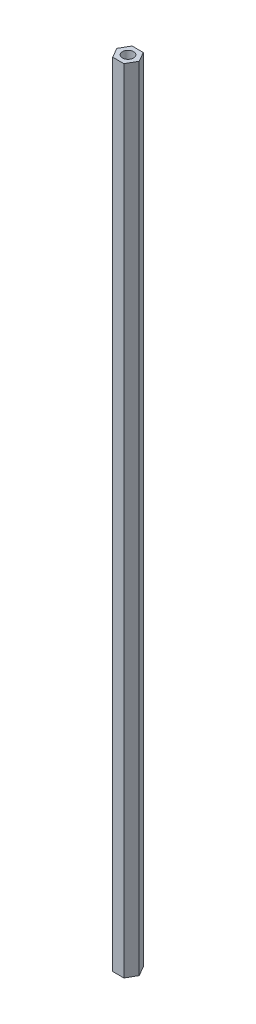
SolidWorks part; units mm, degrees
ref_plane "Front Plane" through (0, 0, 0) normal (0, 0, 1) x (1, 0, 0)
ref_plane "Top Plane" through (0, 0, 0) normal (0, 1, 0) x (1, 0, 0)
ref_plane "Right Plane" through (0, 0, 0) normal (1, 0, 0) x (0, 0, -1)
sketch "Sketch1" plane through (0, 0, 0) normal (0, 1, 0) x (1, 0, 0)
  line L1 (2.0207, 3.5) -> (-2.0207, 3.5)
  line L2 (-2.0207, 3.5) -> (-4.0415, 0)
  line L3 (-4.0415, 0) -> (-2.0207, -3.5)
  line L4 (-2.0207, -3.5) -> (2.0207, -3.5)
  line L5 (2.0207, -3.5) -> (4.0415, 0)
  line L6 (4.0415, 0) -> (2.0207, 3.5)
  circle A0 centre (0, 0) radius 3.5 construction
  circle A1 centre (0, 0) radius 2
  dimension "D1" = 4
  dimension "D2" = 7
extrude "Boss-Extrude1" add sketch "Sketch1" along normal blind 286
